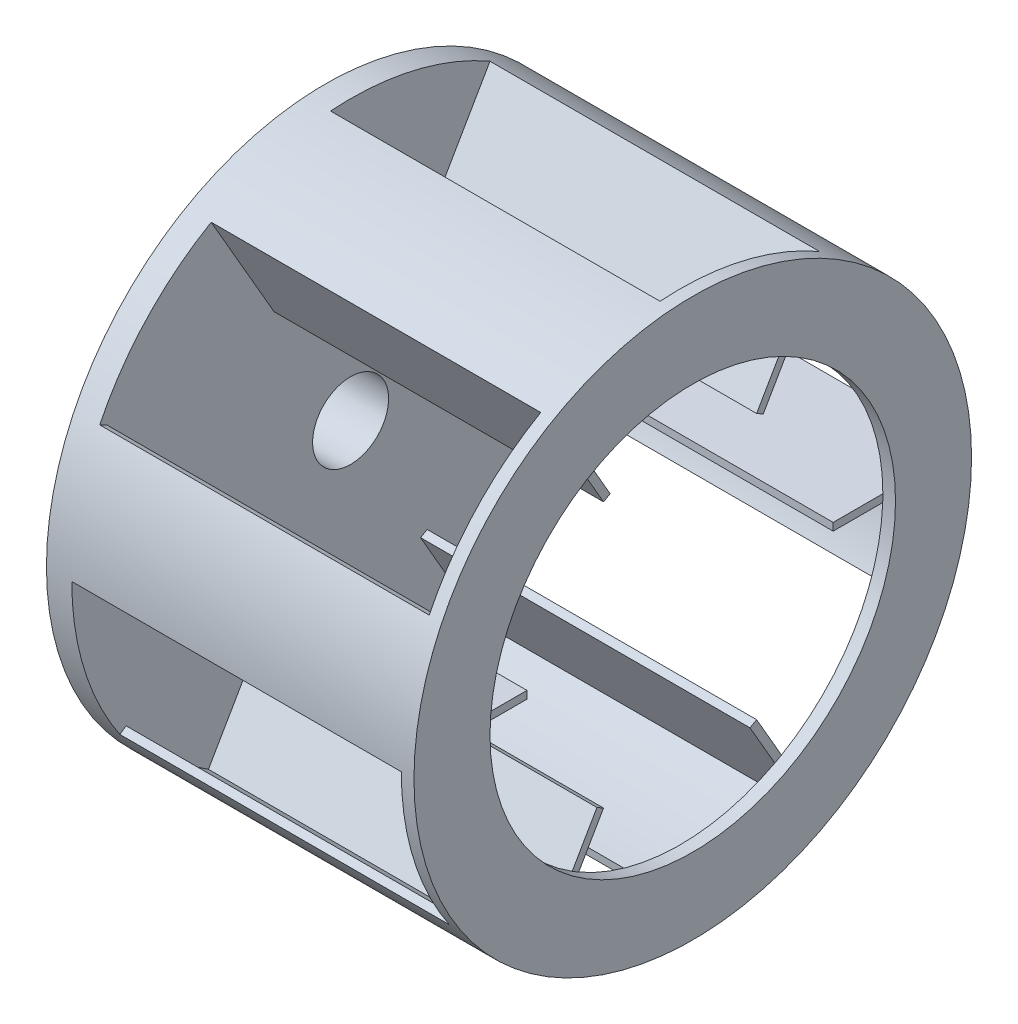
SolidWorks part; units mm, degrees
ref_plane "Front Plane" through (0, 0, 0) normal (0, 0, 1) x (1, 0, 0)
ref_plane "Top Plane" through (0, 0, 0) normal (0, 1, 0) x (1, 0, 0)
ref_plane "Right Plane" through (0, 0, 0) normal (1, 0, 0) x (0, 0, -1)
sketch "Sketch1" plane through (0, 0, 0) normal (1, 0, 0) x (0, 0, -1)
  circle A0 centre (0, 0) radius 5.5
  dimension "D1" = 11
extrude "Boss-Extrude1" add sketch "Sketch1" along normal mid plane 0.5
sketch "Sketch2" plane through (-0.25, 0, 0) normal (-1, 0, 0) x (0, 0, 1)
  circle A0 centre (0, 0) radius 1.5
  dimension "D1" = 3
extrude "Boss-Extrude2" add sketch "Sketch2" along normal blind 2.5
sketch "Sketch3" plane through (-2.75, 0, 0) normal (-1, 0, 0) x (0, 0, 1)
  circle A0 centre (0, 0) radius 0.75
  dimension "D1" = 1.5
extrude "Cut-Extrude1" cut sketch "Sketch3" against normal through all
sketch "Sketch4" plane through (0.25, 0, 0) normal (1, 0, 0) x (0, 0, -1)
  line L0 (-5.5, 0) -> (-3.02, 0)
  line L1 (-3.02, 0) -> (-3.02, 0.15)
  line L2 (-3.02, 0.15) -> (-5.3479, 0.15)
  line L3 (-4.9487, 2.4) -> (-4.8138, 2.3345)
  circle A0 centre (0, 0) radius 5.5 construction
  circle A1 centre (0, 0) radius 5.5
  arc A2 (-4.8138, 2.3345) -> (-5.3479, 0.15) centre (0, 0) ccw
  circle A4 centre (0, 0) radius 5.35 construction
  arc A5 (-4.9487, 2.4) -> (-5.5, 0) centre (0, 0) ccw
  point P10 (5.35, 0)
  circle M8 centre (0, 0) radius 5.5
  dimension "D2" = 0.15
  dimension "D3" = 2.4
  dimension "D4" = 2.48
  dimension "D1" = 0.15
extrude "Boss-Extrude3" add sketch "Sketch4" along normal blind 6.5 contours A2 L3 L0 L1 L2 M8
pattern_circular "CirPattern1" count 6 over 360 about axis through (0, 0, 0) along (1, 0, 0) of "Boss-Extrude3"
sketch "Sketch5" plane through (6.75, 0, 0) normal (1, 0, 0) x (0, 0, -1)
  circle A0 centre (0, 0) radius 4
  circle A2 centre (0, 0) radius 5.5
  arc A3 (-4.5528, -3.0857) -> (-2.75, -4.7631) centre (0, 0) ccw construction
  dimension "D1" = 8
extrude "Boss-Extrude6" add sketch "Sketch5" along normal blind 0.25
